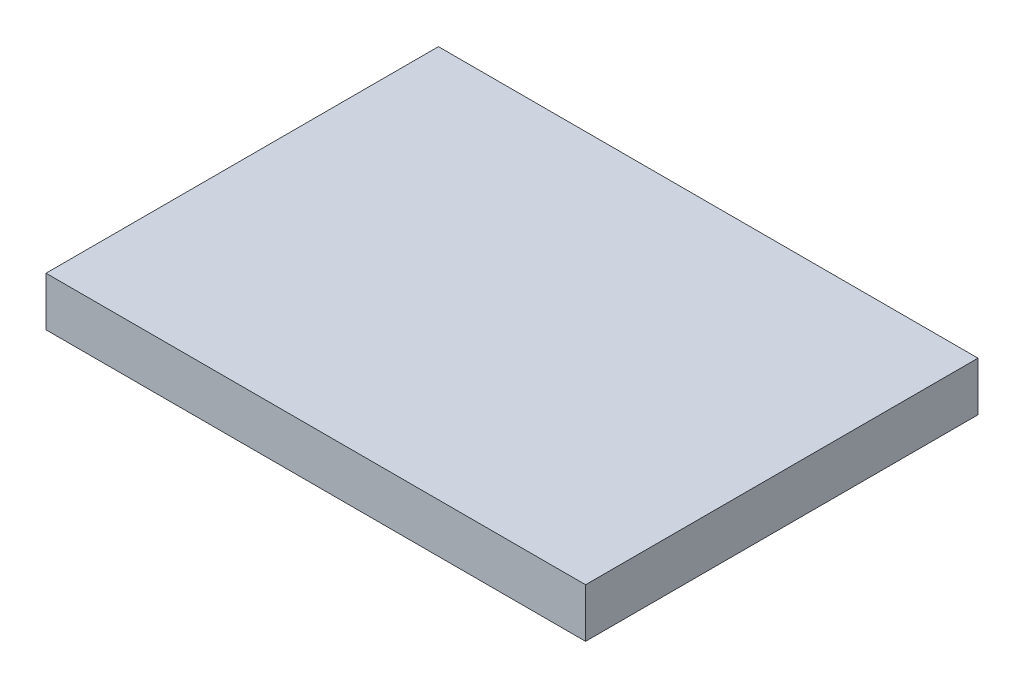
SolidWorks part; units mm, degrees
ref_plane "Front Plane" through (0, 0, 0) normal (0, 0, 1) x (1, 0, 0)
ref_plane "Top Plane" through (0, 0, 0) normal (0, 1, 0) x (1, 0, 0)
ref_plane "Right Plane" through (0, 0, 0) normal (1, 0, 0) x (0, 0, -1)
sketch "Sketch1" plane through (0, 0, 0) normal (0, 1, 0) x (1, 0, 0)
  line L1 (0, 0) -> (34.925, 0)
  line L2 (0, 0) -> (0, 25.4)
  line L3 (0, 25.4) -> (34.925, 25.4)
  line L4 (34.925, 0) -> (34.925, 25.4)
  dimension "D1" = 25.4
  dimension "D2" = 34.925
extrude "Boss-Extrude1" add sketch "Sketch1" along normal blind 3.175
